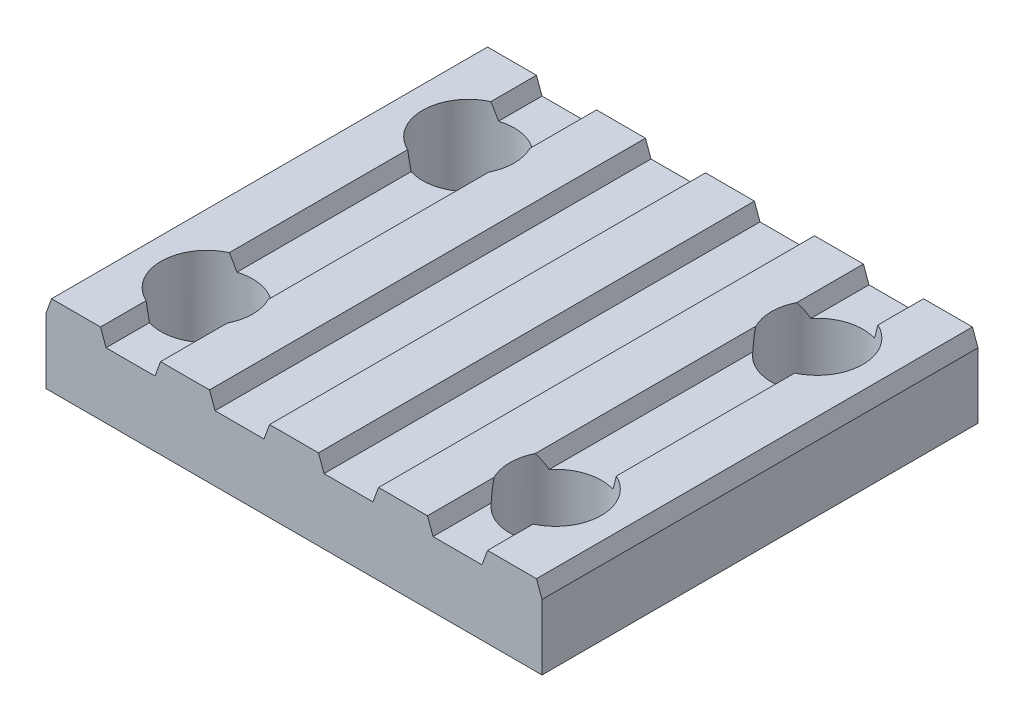
SolidWorks part; units mm, degrees
ref_plane "Front Plane" through (0, 0, 0) normal (0, 0, 1) x (1, 0, 0)
ref_plane "Top Plane" through (0, 0, 0) normal (0, 1, 0) x (1, 0, 0)
ref_plane "Right Plane" through (0, 0, 0) normal (1, 0, 0) x (0, 0, -1)
sketch "Sketch1" plane through (0, 0, 0) normal (0, 0, 1) x (1, 0, 0)
  line L0 (-11.3774, 1.5) -> (-11.1226, 2.2)
  line L1 (11.3774, -1.5) -> (-11.3774, -1.5)
  line L4 (-11.3774, -1.5) -> (-11.3774, 1.5)
  line L5 (-11.3774, 1.5) -> (11.3774, -1.5) construction
  line L6 (11.3774, 1.5) -> (-11.3774, -1.5) construction
  line L7 (-11.1226, 2.2) -> (-8.8774, 2.2)
  line L8 (-8.8774, 2.2) -> (-8.6226, 1.5)
  line L9 (-11.3774, 1.5) -> (-8.6226, 1.5) construction
  line L10 (-6.3774, 1.5) -> (-6.1226, 2.2)
  line L11 (-6.1226, 2.2) -> (-3.8774, 2.2)
  line L12 (-3.8774, 2.2) -> (-3.6226, 1.5)
  line L13 (-10, 1.5) -> (-10, 2.2) construction
  line L15 (-8.6226, 1.5) -> (-6.3774, 1.5)
  line L16 (-3.6226, 1.5) -> (-1.3774, 1.5)
  line L17 (-1.3774, 1.5) -> (-1.1226, 2.2)
  line L18 (-1.1226, 2.2) -> (1.1226, 2.2)
  line L19 (1.1226, 2.2) -> (1.3774, 1.5)
  line L20 (3.6226, 1.5) -> (3.8774, 2.2)
  line L21 (3.8774, 2.2) -> (6.1226, 2.2)
  line L22 (6.1226, 2.2) -> (6.3774, 1.5)
  line L23 (8.6226, 1.5) -> (8.8774, 2.2)
  line L24 (8.8774, 2.2) -> (11.1226, 2.2)
  line L25 (11.1226, 2.2) -> (11.3774, 1.5)
  line L26 (1.3774, 1.5) -> (3.6226, 1.5)
  line L27 (6.3774, 1.5) -> (8.6226, 1.5)
  line L29 (13.8774, 2.2) -> (16.1226, 2.2) [skipped]
  line L30 (13.6226, 1.5) -> (13.8774, 2.2) [skipped]
  line L31 (16.1226, 2.2) -> (16.3774, 1.5) [skipped]
  line L32 (11.3774, 1.5) -> (11.3774, -1.5)
  point P0 (0, 0)
  point P2 (0, 0)
  dimension "D1" = 3
  dimension "D2" = 3.7
  dimension "D3" = 40
  dimension "D7" = 5
  dimension "D6" = 2
extrude "Boss-Extrude1" add sketch "Sketch1" along normal mid plane 20
sketch "Sketch2" plane through (0, -1.5, 0) normal (0, -1, 0) x (1, 0, 0)
  line L0 (-11.516, 0) -> (11.3774, 0) construction
  line L1 (2.035, 0) -> (-2.035, 0) construction
  line L2 (11.3774, 10) -> (11.3774, -10) construction
  line L3 (0, 10) -> (0, -10) construction
  line L4 (-11.3774, 10) -> (11.3774, 10) construction
  line L5 (-11.3774, -10) -> (11.3774, -10) construction
  circle A0 centre (-8, -6) radius 2.1
  circle A1 centre (8, -6) radius 2.1
  circle A2 centre (8, 6) radius 2.1
  circle A3 centre (-8, 6) radius 2.1
  dimension "D1" = 16
  dimension "D2" = 12
  dimension "D3" = 4.2
extrude "Cut-Extrude1" cut sketch "Sketch2" against normal through all
